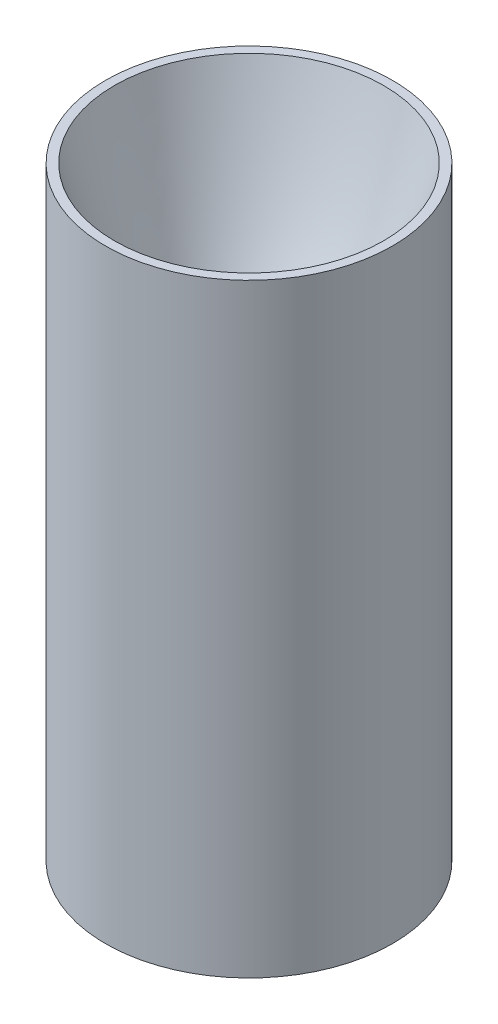
SolidWorks part; units mm, degrees
material "AISI 1020"
ref_plane "Front Plane" through (0, 0, 0) normal (0, 0, 1) x (1, 0, 0)
ref_plane "Top Plane" through (0, 0, 0) normal (0, 1, 0) x (1, 0, 0)
ref_plane "Right Plane" through (0, 0, 0) normal (1, 0, 0) x (0, 0, -1)
sketch "Sketch1" plane through (0, 0, 0) normal (0, 0, 1) x (1, 0, 0)
  line L0 (-0.0055, 165.816) -> (-0.0055, -134.6871) construction
  line L1 (71.7275, 109.9275) -> (76.49, 109.9275)
  line L4 (53.8815, -59.7275) -> (53.8815, -212.1275)
  line L9 (76.49, 109.9275) -> (76.49, -212.1275)
  line L10 (76.49, -212.1275) -> (53.8815, -212.1275)
  spline S0 degree 2 poles (26.7953, 6.5094) (49.2614, 34.6361) (71.7275, 109.9275) knots 0 0 0 1 1 1 construction
  spline S1 degree 2 poles (26.7953, 6.5094) (49.2614, 34.6361) (71.7275, 109.9275) knots 0 0 0 1 1 1
  spline S2 degree 4 poles (24.1269, -0.7179) (24.126, -0.7018) (24.1243, -0.6738) (24.121, -0.6546) (24.115, -0.5166) (24.1058, -0.4369) (24.0994, -0.1066) (24.0979, 0.0018) (24.102, 0.2678) (24.1085, 0.4272) (24.1205, 0.6469) (24.1414, 0.9016) (24.1752, 1.2027) (24.2265, 1.5422) (24.2905, 1.8812) (24.3671, 2.2165) (24.4563, 2.5494) (24.5577, 2.8783) (24.6716, 3.2035) (24.7972, 3.5238) (24.9353, 3.8398) (25.0841, 4.1494) (25.246, 4.4549) (25.4165, 4.7515) (25.6025, 5.0459) (25.7918, 5.3257) (26.0044, 5.6109) (26.1789, 5.8331) (26.3663, 6.0501) (26.5046, 6.2088) (26.757, 6.4728) (26.837, 6.5526) (27.1016, 6.806) (27.1881, 6.8783) (27.2854, 6.9667) (27.3038, 6.9803) (27.3264, 7.0004) knots 0 0 0 0 0 0.005192 0.010384 0.020768 0.041536 0.082569 0.102427 0.122284 0.142142 0.162 0.201716 0.241431 0.281147 0.320863 0.360578 0.400294 0.44001 0.479725 0.519441 0.559156 0.598872 0.638588 0.678303 0.718019 0.757735 0.79745 0.837166 0.857024 0.876882 0.916597 0.958047 0.979024 0.989512 1 1 1 1 1 construction
  spline S3 degree 4 poles (24.0991, 0.0002) (24.0991, 0.0361) (24.0996, 0.1103) (24.102, 0.2678) (24.1085, 0.4272) (24.1205, 0.6469) (24.1414, 0.9016) (24.1752, 1.2027) (24.2265, 1.5422) (24.2905, 1.8812) (24.3671, 2.2165) (24.4563, 2.5494) (24.5577, 2.8783) (24.6716, 3.2035) (24.7972, 3.5238) (24.9353, 3.8398) (25.0841, 4.1494) (25.246, 4.4549) (25.4165, 4.7515) (25.6025, 5.0459) (25.7918, 5.3257) (26.0044, 5.6109) (26.1789, 5.8331) (26.3663, 6.0501) (26.5046, 6.2088) (26.6704, 6.3823) (26.7445, 6.4586) (26.7953, 6.5094) knots 0.082569 0.082569 0.082569 0.082569 0.082569 0.102427 0.122284 0.142142 0.162 0.201716 0.241431 0.281147 0.320863 0.360578 0.400294 0.44001 0.479725 0.519441 0.559156 0.598872 0.638588 0.678303 0.718019 0.757735 0.79745 0.837166 0.857024 0.876882 0.916597 0.916597 0.916597 0.916597 0.916597
  spline S4 degree 4 poles (24.2082, 2.808) (24.2014, 2.7166) (24.1882, 2.5518) (24.1642, 2.1754) (24.1352, 1.6881) (24.1148, 1.1018) (24.103, 0.6556) (24.0988, 0.1104) (24.0988, -0.0999) (24.102, -0.543) (24.1083, -0.824) (24.1178, -1.1947) (24.1304, -1.5133) (24.1462, -1.8618) (24.1652, -2.1935) (24.1928, -2.6179) (24.2323, -3.1219) (24.3033, -3.8798) (24.4231, -4.8863) (24.5995, -6.0566) (24.8509, -7.385) (25.1518, -8.7034) (25.5018, -10.0095) (25.9004, -11.3017) (26.3469, -12.5779) (26.841, -13.8367) (27.3817, -15.076) (27.9685, -16.2944) (28.6001, -17.4898) (29.2765, -18.6611) (29.9954, -19.8056) (30.758, -20.9237) (31.4592, -21.8743) (32.0887, -22.6733) (32.6241, -23.3203) (33.0723, -23.8398) (33.5085, -24.3297) (33.9358, -24.7883) (34.2456, -25.1137) (34.6121, -25.4859) (34.7661, -25.6398) (35.1509, -26.0187) (35.4776, -26.3286) (35.905, -26.7273) (36.2395, -27.0242) (36.5192, -27.2707) (36.6465, -27.3798) (36.7148, -27.4387) (36.7496, -27.4686) knots 0 0 0 0 0 0.010393 0.020785 0.041571 0.062104 0.072371 0.082638 0.092575 0.102512 0.112449 0.122387 0.132324 0.142261 0.152198 0.162135 0.18201 0.201884 0.241633 0.281382 0.32113 0.360879 0.400628 0.440377 0.480126 0.519874 0.559623 0.599372 0.639121 0.67887 0.718618 0.758367 0.798116 0.81799 0.837865 0.857739 0.877613 0.897488 0.907425 0.917362 0.927629 0.937896 0.958429 0.979215 0.989607 0.994804 1 1 1 1 1 construction
  spline S5 degree 4 poles (24.0991, 0.0002) (24.0991, -0.0704) (24.0996, -0.2134) (24.102, -0.543) (24.1083, -0.824) (24.1178, -1.1947) (24.1304, -1.5133) (24.1462, -1.8618) (24.1652, -2.1935) (24.1928, -2.6179) (24.2323, -3.1219) (24.3033, -3.8798) (24.4231, -4.8863) (24.5995, -6.0566) (24.8509, -7.385) (25.1518, -8.7034) (25.5018, -10.0095) (25.9004, -11.3017) (26.3469, -12.5779) (26.841, -13.8367) (27.3817, -15.076) (27.9685, -16.2944) (28.6001, -17.4898) (29.2765, -18.6611) (29.9954, -19.8056) (30.758, -20.9237) (31.4592, -21.8743) (32.0887, -22.6733) (32.6241, -23.3203) (33.0723, -23.8398) (33.5085, -24.3297) (33.9358, -24.7883) (34.2456, -25.1137) (34.5369, -25.4095) (34.6364, -25.5098) (34.6863, -25.5597) knots 0.082638 0.082638 0.082638 0.082638 0.082638 0.092575 0.102512 0.112449 0.122387 0.132324 0.142261 0.152198 0.162135 0.18201 0.201884 0.241633 0.281382 0.32113 0.360879 0.400628 0.440377 0.480126 0.519874 0.559623 0.599372 0.639121 0.67887 0.718618 0.758367 0.798116 0.81799 0.837865 0.857739 0.877613 0.897488 0.907425 0.917362 0.917362 0.917362 0.917362 0.917362
  spline S6 degree 1 poles (34.6863, -25.5597) (43.2939, -34.1673) knots 0 0 1 1 construction
  spline S7 degree 1 poles (34.6863, -25.5597) (43.2939, -34.1673) knots 0 0 1 1
  spline S8 degree 4 poles (53.7724, -62.5352) (53.7792, -62.4464) (53.7924, -62.2737) (53.8104, -62.0016) (53.8309, -61.6599) (53.848, -61.2921) (53.8616, -60.9658) (53.8717, -60.5752) (53.8784, -60.2939) (53.8818, -59.8332) (53.8818, -59.6304) (53.8786, -59.1816) (53.8723, -58.9048) (53.8628, -58.5326) (53.8502, -58.2128) (53.8304, -57.7816) (53.8004, -57.281) (53.7562, -56.688) (53.6773, -55.8485) (53.5774, -55.0082) (53.4567, -54.1724) (53.2868, -53.1724) (53.0921, -52.1774) (52.8664, -51.1885) (52.61, -50.2075) (52.3293, -49.2331) (52.0243, -48.266) (51.6335, -47.1491) (51.1395, -45.8904) (50.5987, -44.651) (50.0121, -43.4327) (49.3801, -42.2371) (48.7041, -41.0662) (47.9845, -39.921) (47.2231, -38.8041) (46.5199, -37.8515) (45.8935, -37.0557) (45.3528, -36.4034) (44.9151, -35.8942) (44.5148, -35.447) (44.1815, -35.0846) (43.8739, -34.7603) (43.6741, -34.5515) (43.3653, -34.2383) (43.2159, -34.0889) (42.8277, -33.7066) (42.5041, -33.3998) (42.0741, -32.9986) (41.7412, -32.7033) (41.4607, -32.4559) (41.3338, -32.3472) (41.2653, -32.2883) (41.2305, -32.2583) knots 0 0 0 0 0 0.010393 0.020785 0.031178 0.041571 0.051838 0.062104 0.072371 0.082638 0.092575 0.102512 0.112449 0.122387 0.132324 0.142261 0.162135 0.18201 0.201884 0.241633 0.261507 0.281382 0.32113 0.360879 0.380754 0.400628 0.440377 0.480126 0.519874 0.559623 0.599372 0.639121 0.67887 0.718618 0.758367 0.798116 0.81799 0.837865 0.857739 0.877613 0.887551 0.897488 0.907425 0.917362 0.927629 0.937896 0.958429 0.979215 0.989607 0.994804 1 1 1 1 1 construction
  spline S9 degree 4 poles (53.8815, -59.7275) (53.8815, -59.657) (53.881, -59.5154) (53.8786, -59.1816) (53.8723, -58.9048) (53.8628, -58.5326) (53.8502, -58.2128) (53.8304, -57.7816) (53.8004, -57.281) (53.7562, -56.688) (53.6773, -55.8485) (53.5774, -55.0082) (53.4567, -54.1724) (53.2868, -53.1724) (53.0921, -52.1774) (52.8664, -51.1885) (52.61, -50.2075) (52.3293, -49.2331) (52.0243, -48.266) (51.6335, -47.1491) (51.1395, -45.8904) (50.5987, -44.651) (50.0121, -43.4327) (49.3801, -42.2371) (48.7041, -41.0662) (47.9845, -39.921) (47.2231, -38.8041) (46.5199, -37.8515) (45.8935, -37.0557) (45.3528, -36.4034) (44.9151, -35.8942) (44.5148, -35.447) (44.1815, -35.0846) (43.8739, -34.7603) (43.6741, -34.5515) (43.4444, -34.3185) (43.3438, -34.2172) (43.2939, -34.1673) knots 0.082638 0.082638 0.082638 0.082638 0.082638 0.092575 0.102512 0.112449 0.122387 0.132324 0.142261 0.162135 0.18201 0.201884 0.241633 0.261507 0.281382 0.32113 0.360879 0.380754 0.400628 0.440377 0.480126 0.519874 0.559623 0.599372 0.639121 0.67887 0.718618 0.758367 0.798116 0.81799 0.837865 0.857739 0.877613 0.887551 0.897488 0.907425 0.917362 0.917362 0.917362 0.917362 0.917362
  spline S10 degree 2 poles (36.8348, 6.4922) (58.683, 41.9569) (81.7275, 109.9275) knots 0.244621 0.244621 0.244621 0.999364 0.999364 0.999364 construction
  dimension "D1" = 24.1046
  dimension "D2" = 53.8871
  dimension "D3" = 152.4
  dimension "D4" = 322.055
  dimension "D5" = 4.7625
  dimension "D7" = 24.0991
  dimension "D8" = 26.7953
  dimension "D9" = 34.6863
  dimension "D10" = 0.0002
revolve "Revolve2" add sketch "Sketch1" angle 360 about L0
sketch "Sketch2" plane through (0, -212.1275, 0) normal (0, -1, 0) x (1, 0, 0)
  line L1 (65.2, 0) -> (65.2, -54.0399) construction
  circle A3 centre (0, 0) radius 65.2 construction
  dimension "D1" = 130.4
hole_wizard "3/8-24 Tapped Hole1" positions "Sketch3" profile "Sketch4" tap size "3/8-24" standard "ANSI Inch"
sketch "Sketch3" plane through (0, -212.1275, 0) normal (0, -1, 0) x (-1, 0, 0)
  point P0 (-65.2, 0)
sketch "Sketch4" plane through (65.2, -212.1275, 0) normal (1, 0, 0) x (0, 0, -1)
  line L0 (0, 0) -> (0, 27.5335)
  line L1 (0, 27.5335) -> (4.2164, 25)
  line L2 (4.2164, 25) -> (4.2164, 0)
  line L5 (4.2164, 0) -> (0, 0)
  line L10 (0, 27.5335) -> (-4.2164, 25) construction
  line L11 (0, -6.35) -> (0, 107.95) construction
  dimension "Tap Drill Dia." = 8.4328
  dimension "Tap Drill Depth" = 25
  dimension "Drill Angle" = 118
cosmetic thread "Hole Thread1" parameters "D1"=20, "D2"=9.525
sketch "Sketch5" plane through (0, 0, 0) normal (0, 0, 1) x (1, 0, 0)
  line L0 (0, -228.487) -> (-0.0055, 109.9275) construction
  line L1 (71.7275, 109.9275) -> (-71.7386, 109.9275) construction
pattern_circular "CirPattern1" count 8 over 360 about axis through (0, -228.487, 0) along (0, 1, 0) of "3/8-24 Tapped Hole1"
cosmetic thread "Hole Thread2" parameters "D1"=20, "D2"=9.525
cosmetic thread "Hole Thread3" parameters "D1"=20, "D2"=9.525
cosmetic thread "Hole Thread4" parameters "D1"=20, "D2"=9.525
cosmetic thread "Hole Thread5" parameters "D1"=20, "D2"=9.525
cosmetic thread "Hole Thread6" parameters "D1"=20, "D2"=9.525
cosmetic thread "Hole Thread7" parameters "D1"=20, "D2"=9.525
cosmetic thread "Hole Thread8" parameters "D1"=20, "D2"=9.525
sketch "Sketch8" plane through (0, -212.1275, 0) normal (0, -1, 0) x (1, 0, 0)
  circle A0 centre (0, 0) radius 53.8815 construction
  circle A1 centre (0, 0) radius 76.49 construction
  circle A2 centre (0, 0) radius 65.2002 construction
  dimension "D1" = 107.7631
  dimension "D2" = 130.4004
  dimension "D3" = 152.98
sketch "Sketch9" plane through (0, -212.1275, 0) normal (0, -1, 0) x (1, 0, 0)
  circle A0 centre (0, 0) radius 53.8815
  circle A1 centre (0, 0) radius 56.8815
  dimension "D1" = 3
extrude "Cut-Extrude1" cut sketch "Sketch9" against normal blind 6
